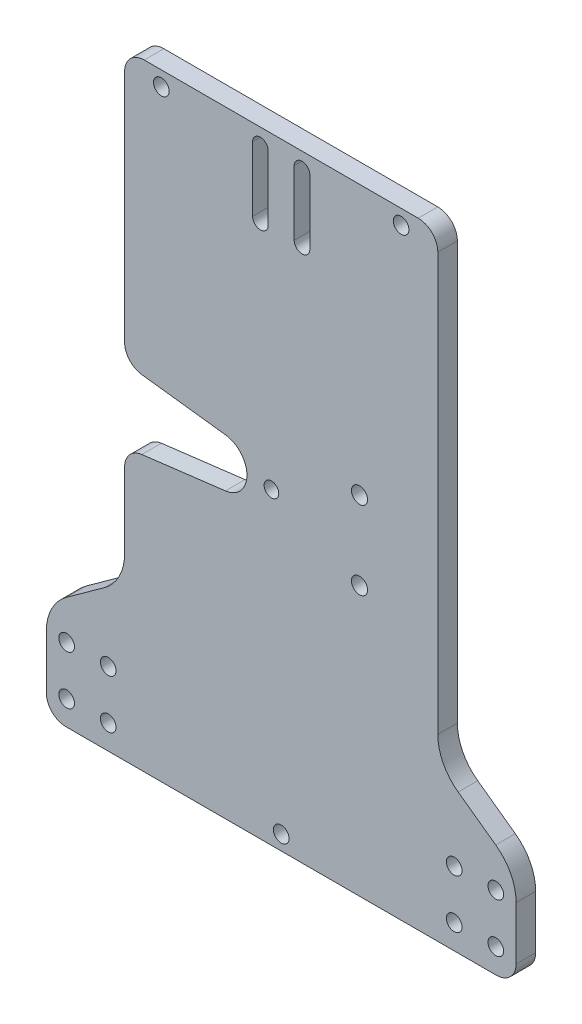
SolidWorks part; units mm, degrees
material "Acrylic (Medium-high impact)"
ref_plane "Front Plane" through (0, 0, 0) normal (0, 0, 1) x (1, 0, 0)
ref_plane "Top Plane" through (0, 0, 0) normal (0, 1, 0) x (1, 0, 0)
ref_plane "Right Plane" through (0, 0, 0) normal (1, 0, 0) x (0, 0, -1)
sketch "Sketch1" plane through (0, 0, 0) normal (0, 0, 1) x (1, 0, 0)
  line L0 (-0.75, 63) -> (96.75, 63) construction
  line L1 (0, 0) -> (96, 0)
  line L2 (0, 0) -> (0, 20)
  line L3 (16, 63) -> (36, 63) construction
  line L4 (96, 20) -> (80, 31.52)
  line L5 (0, 20) -> (16, 31.52)
  line L7 (96, 0) -> (96, 20)
  line L8 (48, 0) -> (48, 63) construction
  line L9 (16, 126) -> (16, 70.5)
  line L11 (16, 55.5) -> (16, 31.52)
  line L12 (80, 126) -> (80, 31.52)
  line L13 (16, 126) -> (80, 126)
  line L14 (12.65, 10) -> (4.15, 10) construction
  line L15 (4.15, 5) -> (12.65, 5) construction
  line L16 (4.15, 5) -> (4.15, 15) construction
  line L17 (4.15, 15) -> (12.65, 15) construction
  line L18 (12.65, 5) -> (12.65, 15) construction
  line L19 (48, 126) -> (48, 122.6) construction
  line L20 (43.75, 122.6) -> (52.25, 122.6) construction
  line L21 (43.75, 122.6) -> (43.75, 109.4) construction
  line L22 (43.75, 109.4) -> (52.25, 109.4) construction
  line L23 (52.25, 122.6) -> (52.25, 109.4) construction
  line L24 (43.75, 116) -> (52.25, 116) construction
  line L25 (43.75, 122.6) -> (43.75, 109.4) construction
  line L26 (45.35, 122.6) -> (45.35, 109.4)
  line L27 (42.15, 122.6) -> (42.15, 109.4)
  line L28 (52.25, 109.4) -> (52.25, 122.6) construction
  line L29 (50.65, 109.4) -> (50.65, 122.6)
  line L30 (53.85, 109.4) -> (53.85, 122.6)
  line L31 (64, 71) -> (64, 55) construction
  line L32 (71, 63) -> (64, 63) construction
  line L33 (16, 70.5) -> (36.611, 67.9625)
  line L34 (16, 55.5) -> (36.611, 58.0375)
  circle A0 centre (4.15, 5) radius 1.6
  circle A1 centre (12.65, 5) radius 1.6
  circle A2 centre (12.65, 15) radius 1.6
  circle A3 centre (4.15, 15) radius 1.6
  circle A4 centre (91.85, 5) radius 1.6
  circle A5 centre (83.35, 5) radius 1.6
  circle A6 centre (83.35, 15) radius 1.6
  circle A7 centre (91.85, 15) radius 1.6
  circle A8 centre (48, 3) radius 1.6
  circle A9 centre (23.5, 123) radius 1.6
  circle A10 centre (72.5, 123) radius 1.6
  circle A11 centre (64, 71) radius 1.65
  arc A12 (45.35, 122.6) -> (42.15, 122.6) centre (43.75, 122.6) ccw
  arc A13 (42.15, 109.4) -> (45.35, 109.4) centre (43.75, 109.4) ccw
  arc A14 (50.65, 109.4) -> (53.85, 109.4) centre (52.25, 109.4) ccw
  arc A15 (53.85, 122.6) -> (50.65, 122.6) centre (52.25, 122.6) ccw
  circle A16 centre (64, 55) radius 1.65
  circle A17 centre (46, 63) radius 1.5
  arc A19 (36.611, 58.0375) -> (36.611, 67.9625) centre (36, 63) ccw
  point P16 (25, 63)
  point P18 (71, 63)
  point P51 (43.75, 116)
  point P56 (52.25, 116)
  point P66 (26.877, 63)
  dimension "D10" = 3.2
  dimension "D15" = 3.2
  dimension "D19" = 24.5
  dimension "D24" = 3.3
  dimension "D5" = 5
  dimension "D22" = 20
  dimension "D27" = 3
  dimension "D1" = 63
  dimension "D2" = 48
  dimension "D3" = 20
  dimension "D4" = 16
  dimension "D6" = 10
  dimension "D7" = 8.5
  dimension "D8" = 53
  dimension "D9" = 4.15
  dimension "D11" = 8.5
  dimension "D12" = 3
  dimension "D13" = 53
  dimension "D14" = 13.2
  dimension "D16" = 3
  dimension "D17" = 24.5
  dimension "D18" = 3
  dimension "D20" = 63
  dimension "D21" = 32
  dimension "D23" = 16
  dimension "D25" = 10
  dimension "D26" = 15
extrude "Boss-Extrude1" add sketch "Sketch1" along normal blind 4
fillet "Fillet1" radius 4 6 edges at (96, 0, 2) (0, 0, 2) (80, 126, 2) (16, 126, 2) (16, 70.5, 2) (16, 55.5, 2)
fillet "Fillet2" radius 10 4 edges at (96, 20, 2) (0, 20, 2) (80, 31.52, 2) (16, 31.52, 2)
